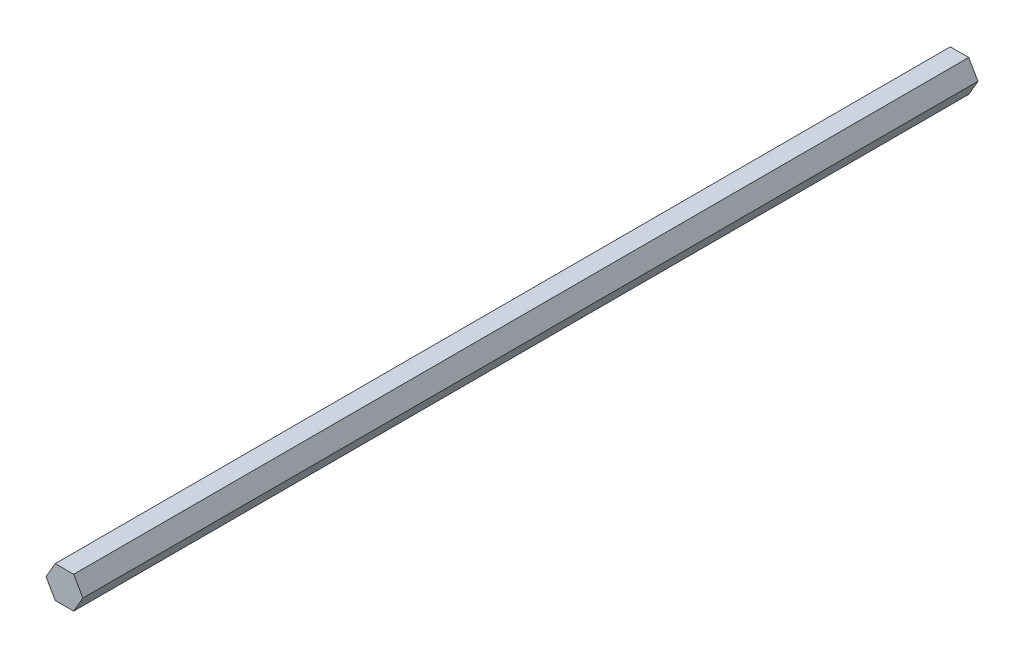
SolidWorks part; units mm, degrees
ref_plane "Front Plane" through (0, 0, 0) normal (0, 0, 1) x (1, 0, 0)
ref_plane "Top Plane" through (0, 0, 0) normal (0, 1, 0) x (1, 0, 0)
ref_plane "Right Plane" through (0, 0, 0) normal (1, 0, 0) x (0, 0, -1)
sketch "Sketch1" plane through (0, 0, 0) normal (0, 0, 1) x (1, 0, 0)
  line L1 (3.6662, 6.35) -> (-3.6662, 6.35)
  line L2 (-3.6662, 6.35) -> (-7.3323, 0)
  line L3 (-7.3323, 0) -> (-3.6662, -6.35)
  line L4 (-3.6662, -6.35) -> (3.6662, -6.35)
  line L5 (3.6662, -6.35) -> (7.3323, 0)
  line L6 (7.3323, 0) -> (3.6662, 6.35)
  circle A0 centre (0, 0) radius 6.35 construction
  point P1 (0.1375, 0.25)
  dimension "D1" = 12.7
extrude "Boss-Extrude1" add sketch "Sketch1" along normal blind 355.6
